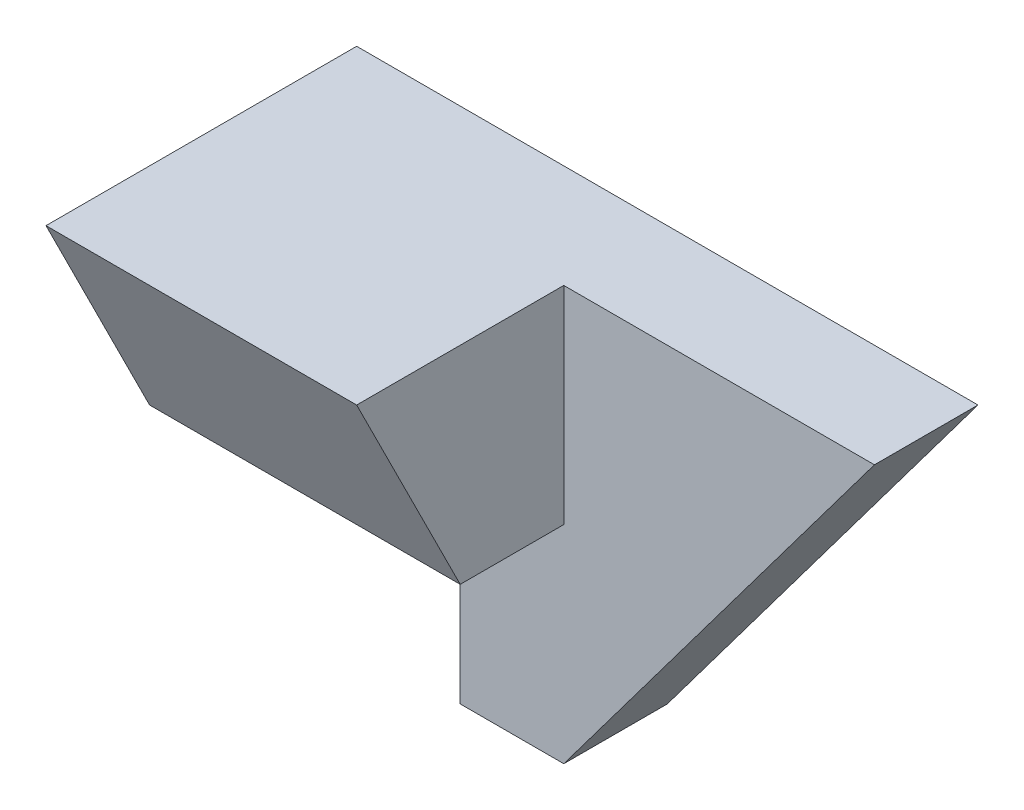
SolidWorks part; units mm, degrees
ref_plane "Płaszczyzna przednia" through (0, 0, 0) normal (0, 0, 1) x (1, 0, 0)
ref_plane "Płaszczyzna górna" through (0, 0, 0) normal (0, 1, 0) x (1, 0, 0)
ref_plane "Płaszczyzna prawa" through (0, 0, 0) normal (1, 0, 0) x (0, 0, -1)
sketch "Szkic1" plane through (0, 0, 0) normal (0, 0, 1) x (1, 0, 0)
  line L0 (0, 0) -> (0, -30)
  line L1 (0, -30) -> (20, -30)
  line L2 (20, -30) -> (20, -40)
  line L3 (20, -40) -> (30, -40)
  line L4 (0, 0) -> (60, 0)
  line L5 (60, 0) -> (30, -40)
  dimension "D1" = 10
  dimension "D2" = 30
  dimension "D3" = 60
  dimension "D4" = 20
extrude "Dodanie-wyciągnięcie1" add sketch "Szkic1" along normal blind 10
sketch "Szkic2" plane through (0, 0, 10) normal (0, 0, 1) x (1, 0, 0)
  line L0 (0, 0) -> (0, -20)
  line L1 (0, 0) -> (0, -30) construction
  line L2 (0, -20) -> (30, -20)
  line L3 (30, -20) -> (30, 0)
  line L4 (60, 0) -> (0, 0) construction
  line L5 (30, 0) -> (0, 0)
  dimension "D1" = 20
extrude "Dodanie-wyciągnięcie2" add sketch "Szkic2" along normal blind 20
sketch "Szkic3" plane through (30, 0, 0) normal (1, 0, 0) x (0, 0, -1)
  line L0 (-30, -20) -> (-20, -20)
  line L1 (-30, -20) -> (-10, -20) construction
  line L2 (-20, -20) -> (-30, 0)
  line L3 (-30, 0) -> (-30, -20)
extrude "Wytnij-wyciągnięcie1" cut sketch "Szkic3" against normal blind 43
